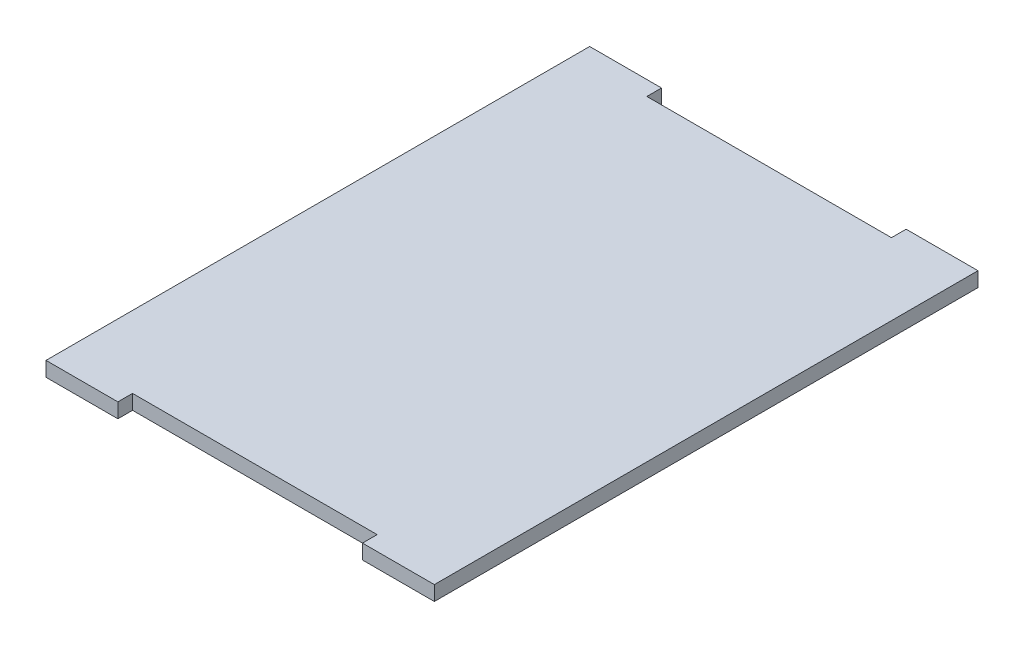
SolidWorks part; units mm, degrees
ref_plane "Front Plane" through (0, 0, 0) normal (0, 0, 1) x (1, 0, 0)
ref_plane "Top Plane" through (0, 0, 0) normal (0, 1, 0) x (1, 0, 0)
ref_plane "Right Plane" through (0, 0, 0) normal (1, 0, 0) x (0, 0, -1)
sketch "Sketch1" plane through (0, 0, 0) normal (0, 1, 0) x (1, 0, 0)
  line L0 (0, 55.565) -> (0, -55.565) construction
  line L1 (-39.69, -55.565) -> (-25, -55.565)
  line L2 (-39.69, -55.565) -> (-39.69, 55.565)
  line L3 (-39.69, 55.565) -> (-25, 55.565)
  line L4 (39.69, -55.565) -> (39.69, 55.565)
  line L5 (-39.69, -55.565) -> (39.69, 55.565) construction
  line L6 (-39.69, 55.565) -> (39.69, -55.565) construction
  line L7 (-25, 55.565) -> (-25, 52.565)
  line L8 (-25, 52.565) -> (25, 52.565)
  line L9 (25, 52.565) -> (25, 55.565)
  line L10 (-39.69, 0) -> (39.69, 0) construction
  line L11 (25, 55.565) -> (39.69, 55.565)
  line L12 (25, -52.565) -> (25, -55.565)
  line L13 (-25, -55.565) -> (-25, -52.565)
  line L14 (-25, -52.565) -> (25, -52.565)
  line L15 (25, -55.565) -> (39.69, -55.565)
  point P0 (0, 0)
  dimension "D1" = 79.38
  dimension "D2" = 111.13
  dimension "D3" = 25
  dimension "D4" = 25
  dimension "D5" = 3
extrude "Boss-Extrude1" add sketch "Sketch1" along normal blind 3
